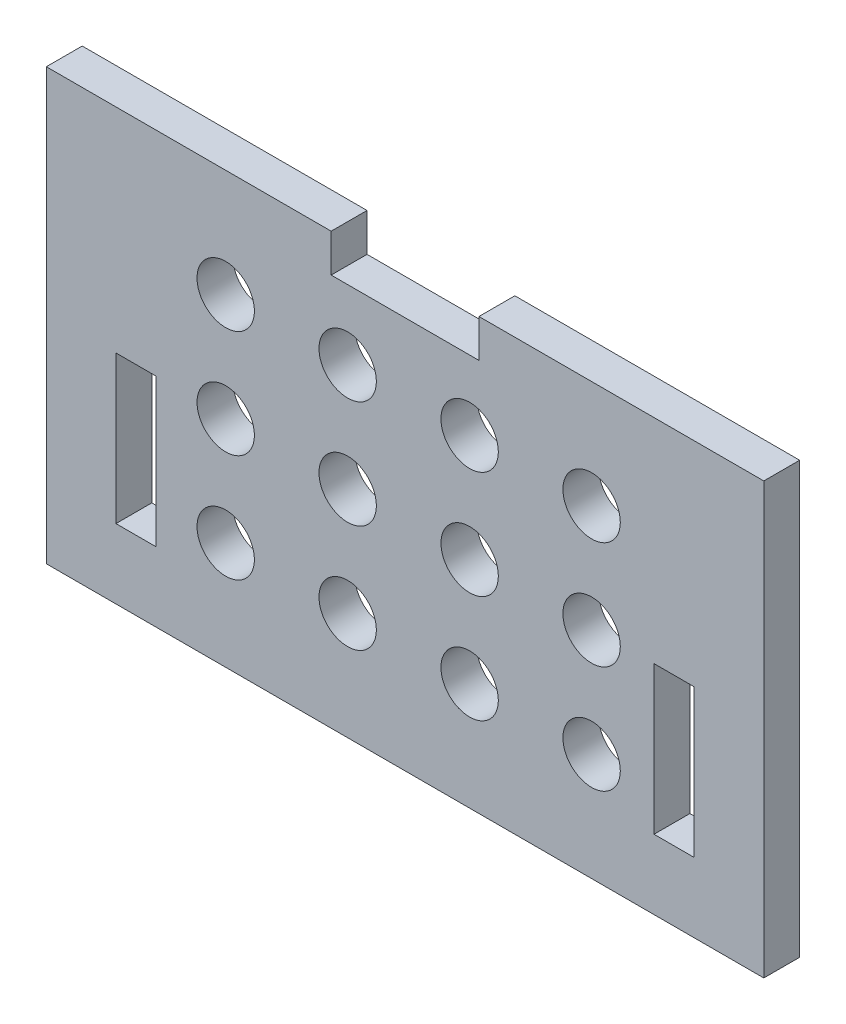
SolidWorks part; units mm, degrees
ref_plane "Спереди" through (0, 0, 0) normal (0, 0, 1) x (1, 0, 0)
ref_plane "Сверху" through (0, 0, 0) normal (0, 1, 0) x (1, 0, 0)
ref_plane "Справа" through (0, 0, 0) normal (1, 0, 0) x (0, 0, -1)
sketch "Sketch1" plane through (0, 0, 0) normal (0, 0, 1) x (1, 0, 0)
  line L0 (50, 55) -> (50, 0) construction
  line L1 (0, 0) -> (100, 0)
  line L2 (0, 0) -> (0, 60)
  line L3 (0, 60) -> (39.7, 60)
  line L4 (100, 0) -> (100, 60)
  line L13 (60.3, 60) -> (100, 60)
  line L18 (9.7, 30.3) -> (9.7, 9.7)
  line L19 (9.7, 9.7) -> (15.3, 9.7)
  line L20 (15.3, 30.3) -> (15.3, 9.7)
  line L21 (9.7, 30.3) -> (15.3, 30.3)
  line L22 (90.3, 9.7) -> (84.7, 9.7)
  line L23 (84.7, 30.3) -> (84.7, 9.7)
  line L24 (90.3, 30.3) -> (84.7, 30.3)
  line L25 (90.3, 30.3) -> (90.3, 9.7)
  line L26 (39.7, 60) -> (39.7, 54.7)
  line L27 (39.7, 54.7) -> (60.3, 54.7)
  line L28 (60.3, 60) -> (60.3, 54.7)
  circle A0 centre (25, 45) radius 4
  circle A1 centre (42, 45) radius 4
  circle A2 centre (59, 45) radius 4
  circle A3 centre (76, 45) radius 4
  circle A4 centre (42, 30) radius 4
  circle A5 centre (59, 30) radius 4
  circle A6 centre (76, 30) radius 4
  circle A7 centre (42, 15) radius 4
  circle A8 centre (59, 15) radius 4
  circle A9 centre (76, 15) radius 4
  circle A10 centre (25, 30) radius 4
  circle A11 centre (25, 15) radius 4
  dimension "D10" = 8
  dimension "D1" = 100
  dimension "D2" = 60
  dimension "D11" = 25
  dimension "D12" = 15
  dimension "D13" = 4
  dimension "D14" = 3
extrude "Boss-Extrude1" add sketch "Sketch1" along normal blind 5
